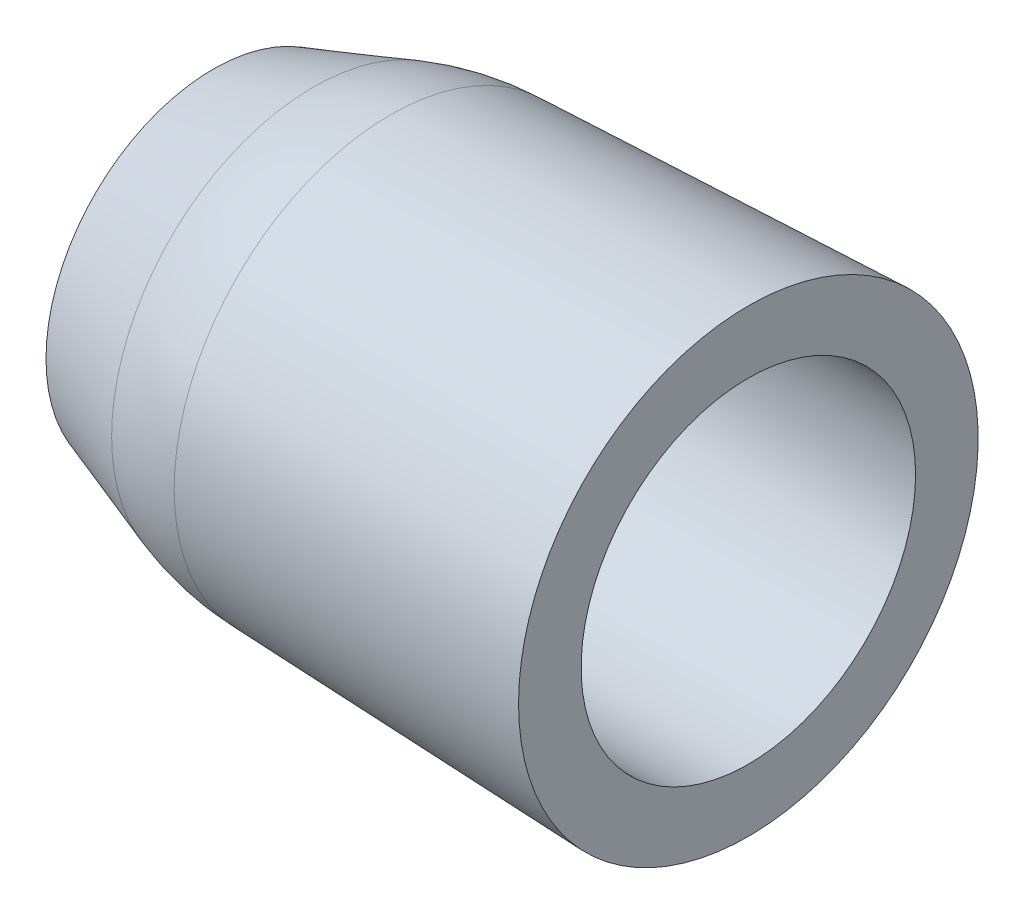
SolidWorks part; units mm, degrees
material "PVC 0.007 Plasticized"
ref_plane "Front Plane" through (0, 0, 0) normal (0, 0, 1) x (1, 0, 0)
ref_plane "Top Plane" through (0, 0, 0) normal (0, 1, 0) x (1, 0, 0)
ref_plane "Right Plane" through (0, 0, 0) normal (1, 0, 0) x (0, 0, -1)
sketch "Sketch2" plane through (0, 0, 0) normal (0, 0, 1) x (1, 0, 0)
  line L0 (-27.8095, 0) -> (-2.4095, 0) construction
  line L1 (-2.4095, 10.9078) -> (-21.2812, 10.1867)
  line L2 (-21.2812, 10.1867) -> (-27.8095, 7.9375)
  line L3 (-27.8095, 7.9375) -> (-27.8095, 0)
  line L4 (-2.4095, 10.9078) -> (-2.4095, 0)
  line L5 (-27.8095, 0) -> (-2.4095, 0)
  line L6 (-27.8095, 0) -> (-2.4095, 0)
  point P5 (0, 0)
  point P7 (-2.4095, 10.9078)
  dimension "D1" = 7.9375
  dimension "D2" = 25.4
revolve "Revolve1" add sketch "Sketch2" angle 360 about L0
sketch "Sketch3" plane through (-2.4095, 0, 0) normal (1, 0, 0) x (0, 0, -1)
  circle A0 centre (0, 0) radius 7.9375
  dimension "D1" = 15.875
extrude "Cut-Extrude1" cut sketch "Sketch3" against normal blind 25.146
fillet "Fillet1" radius 12.7 1 edges at (-21.2812, 0, 10.1867)
